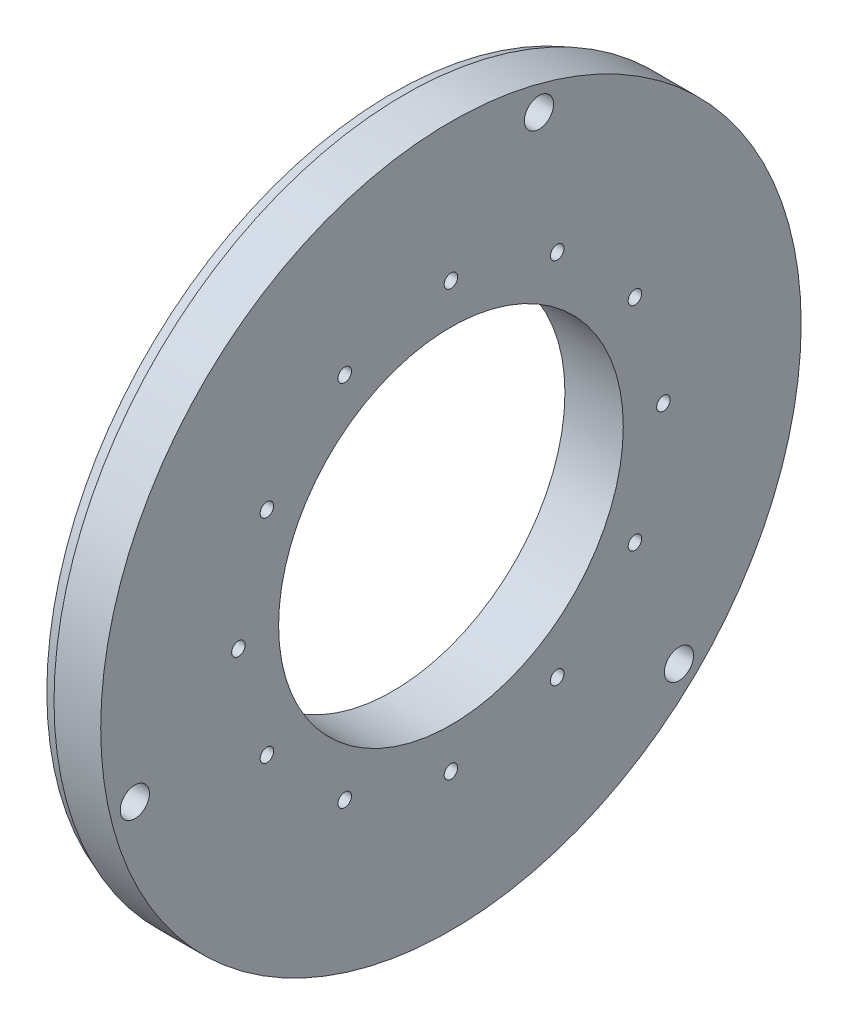
SolidWorks part; units mm, degrees
material "6061 Alloy"
ref_plane "Front Plane" through (0, 0, 0) normal (0, 0, 1) x (1, 0, 0)
ref_plane "Top Plane" through (0, 0, 0) normal (0, 1, 0) x (1, 0, 0)
ref_plane "Right Plane" through (0, 0, 0) normal (1, 0, 0) x (0, 0, -1)
sketch "Sketch1" plane through (0, 0, 0) normal (1, 0, 0) x (0, 0, -1)
  circle A0 centre (0, 0) radius 76.2
  dimension "D1" = 152.4
extrude "Boss-Extrude1" add sketch "Sketch1" along normal blind 12.7
sketch "Sketch2" plane through (12.7, 0, 0) normal (1, 0, 0) x (0, 0, -1)
  circle A0 centre (0, 0) radius 37.5
  dimension "D1" = 75
extrude "Cut-Extrude1" cut sketch "Sketch2" against normal through all
sketch "Sketch7" plane through (12.7, 0, 0) normal (1, 0, 0) x (0, 0, -1)
  circle A0 centre (0, 0) radius 46.228 construction
  dimension "D1" = 92.456
sketch "Sketch8" plane through (12.7, 0, 0) normal (1, 0, 0) x (0, 0, -1)
  circle A0 centre (0, 46.228) radius 1.4732
  circle A1 centre (0, 0) radius 46.228 construction
  dimension "D1" = 2.9464
extrude "Cut-Extrude3" cut sketch "Sketch8" against normal through all
pattern_circular "CirPattern6" count 12 over 360 about axis through (0, 0, 0) along (1, 0, 0) of "Cut-Extrude3"
sketch "Sketch11" plane through (12.7, 0, 0) normal (1, 0, 0) x (0, 0, -1)
  circle A0 centre (19.1597, 68.3534) radius 3.175
  dimension "D1" = 6.35
extrude "Cut-Extrude4" cut sketch "Sketch11" against normal through all
pattern_circular "CirPattern7" count 3 over 360 about axis through (0, 0, 0) along (1, 0, 0) of "Cut-Extrude4"
sketch "Sketch13" plane through (0, 0, 0) normal (-1, 0, 0) x (0, 0, 1)
  circle A0 centre (0, 0) radius 75.2221
  dimension "D1" = 150.4442
extrude "Cut-Extrude5" cut sketch "Sketch13" against normal blind 2.54 flip side to cut
